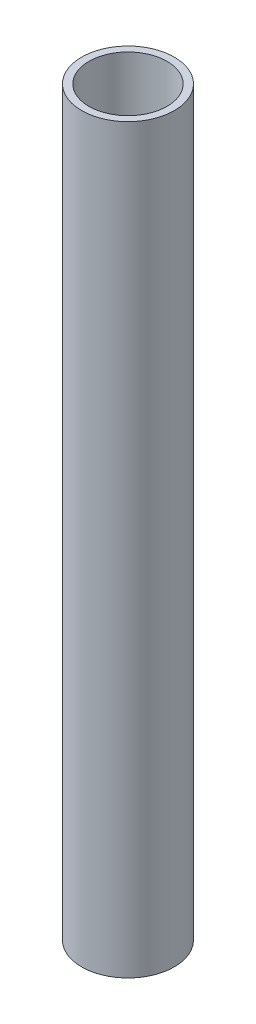
SolidWorks part; units mm, degrees
material "AISI 316 Stainless Steel Sheet (SS)"
ref_plane "Front Plane" through (0, 0, 0) normal (0, 0, 1) x (1, 0, 0)
ref_plane "Top Plane" through (0, 0, 0) normal (0, 1, 0) x (1, 0, 0)
ref_plane "Right Plane" through (0, 0, 0) normal (1, 0, 0) x (0, 0, -1)
sketch "Sketch1" plane through (0, 0, 0) normal (0, 1, 0) x (1, 0, 0)
  circle A0 centre (0, 0) radius 6.35
  circle A1 centre (0, 0) radius 5.35
  dimension "D1" = 12.7
  dimension "D2" = 1
extrude "Boss-Extrude1" add sketch "Sketch1" along normal blind 101.6
